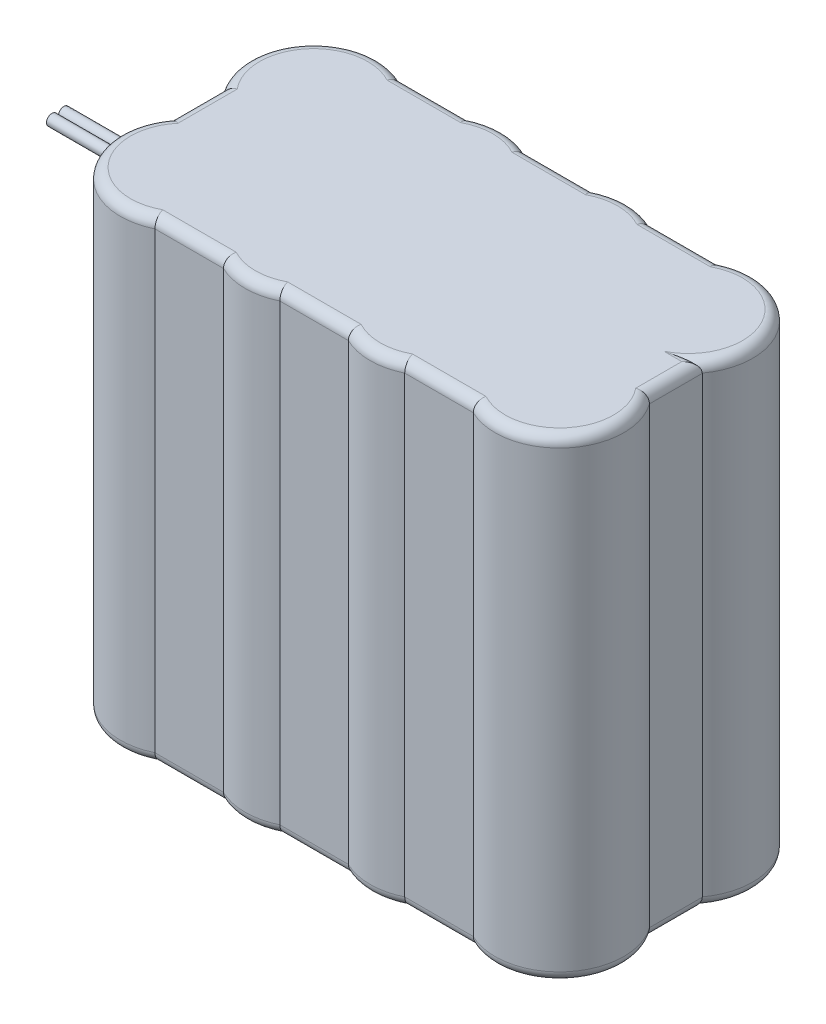
SolidWorks part; units mm, degrees
ref_plane "Front Plane" through (0, 0, 0) normal (0, 0, 1) x (1, 0, 0)
ref_plane "Top Plane" through (0, 0, 0) normal (0, 1, 0) x (1, 0, 0)
ref_plane "Right Plane" through (0, 0, 0) normal (1, 0, 0) x (0, 0, -1)
sketch "Sketch2" plane through (0, 0, 0) normal (0, 1, 0) x (1, 0, 0)
  line L0 (0, 0) -> (0, 185.5089) construction
  line L1 (0, 94.486) -> (-55.52, 94.486) construction
  line L2 (-46.07, 103.936) -> (0, 103.936) construction
  line L3 (0, 102.986) -> (-55.52, 102.986) construction
  line L4 (0, 102.986) -> (0, 85.986) construction
  line L5 (0, 85.986) -> (-55.52, 85.986)
  line L6 (-55.52, 102.986) -> (-55.52, 85.986)
  line L7 (0, 102.986) -> (-55.52, 85.986) construction
  line L8 (0, 85.986) -> (-55.52, 102.986) construction
  line L9 (-55.52, 104.886) -> (-55.52, 121.886)
  line L10 (0, 85.986) -> (18.31, 85.986)
  line L11 (0, 85.986) -> (0, 102.986)
  line L12 (0, 102.986) -> (18.31, 102.986) construction
  line L13 (18.31, 85.986) -> (18.31, 102.986)
  line L14 (18.31, 121.886) -> (18.31, 104.886)
  line L15 (0, 104.886) -> (-55.52, 104.886) construction
  line L16 (0, 104.886) -> (18.31, 104.886) construction
  line L17 (0, 121.886) -> (18.31, 121.886)
  line L18 (0, 121.886) -> (-55.52, 121.886)
  line L20 (16.5224, 100.0168) -> (-53.6623, 100.0168)
  line L21 (16.5224, 100.0168) -> (16.5224, 107.7593)
  line L22 (16.5224, 107.7593) -> (-53.6623, 107.7593)
  line L23 (-53.6623, 100.0168) -> (-53.6623, 107.7593)
  circle A0 centre (-46.07, 94.486) radius 9.45
  circle A1 centre (-27.76, 94.486) radius 9.45
  circle A2 centre (-9.45, 94.486) radius 9.45
  circle A3 centre (8.86, 94.486) radius 9.45
  circle A4 centre (-46.07, 113.386) radius 9.45
  circle A5 centre (-27.76, 113.386) radius 9.45
  circle A6 centre (-9.45, 113.386) radius 9.45
  circle A7 centre (8.86, 113.386) radius 9.45
  dimension "D1" = 18.9
  dimension "D3" = 9.45
  dimension "D4" = 17
  dimension "D2" = 4
extrude "Boss-Extrude1" add sketch "Sketch2" along normal blind 69.5
fillet "Fillet1" radius 1.5 34 edges at (-36.915, 69.5, -121.886) (-27.76, 69.5, -122.836) (-18.605, 69.5, -121.886) (-9.45, 69.5, -122.836) (-0.295, 69.5, -121.886) (16.1325, 69.5, -119.4204) (16.4874, 69.5, -107.7593) (16.5224, 69.5, -103.888) (16.0944, 69.5, -88.406) (-0.295, 69.5, -85.986) (-9.45, 69.5, -85.036) (-18.605, 69.5, -85.986) (-27.76, 69.5, -85.036) (-36.915, 69.5, -85.986) (-53.3425, 69.5, -88.4516) (-53.6623, 69.5, -103.936) (-53.3425, 69.5, -119.4204) (-53.3425, 0, -88.4516) (-36.915, 0, -85.986) (-27.76, 0, -85.036) (-18.605, 0, -85.986) (-9.45, 0, -85.036) (-0.295, 0, -85.986) (16.0944, 0, -88.406) (16.5224, 0, -103.888) (16.4874, 0, -107.7593) (16.1325, 0, -119.4204) (-0.295, 0, -121.886) (-9.45, 0, -122.836) (-18.605, 0, -121.886) (-27.76, 0, -122.836) (-36.915, 0, -121.886) (-53.3425, 0, -119.4204) (-53.6623, 0, -103.936)
ref_plane "Plane1" through (-54.6623, 0, 0) normal (-1, 0, 0) x (0, 0, 1)
sketch "Sketch6" plane through (-54.6623, 0, 0) normal (-1, 0, 0) x (0, 0, 1)
  line L0 (-94.486, 67.5) -> (-94.486, 62.2)
  line L1 (-95.361, 67.5) -> (-93.611, 67.5)
  line L4 (-85.036, 67.5) -> (-103.936, 67.5)
  line L6 (-94.6391, 67.5) -> (-94.3329, 67.5)
  line L9 (-95.286, 67.5) -> (-93.686, 67.5)
  circle A0 centre (-95.361, 66.7) radius 0.8
  circle A1 centre (-93.611, 66.7) radius 0.8
  point P15 (-94.486, 67.5)
  dimension "D1" = 1.75
extrude "Boss-Extrude4" add sketch "Sketch6" along normal blind 10 and the other way blind 10 contours A0 | A1
equation "\"D3@Sketch2\"=18.9/2"
equation "\"WireDiameter\"=0.8"
